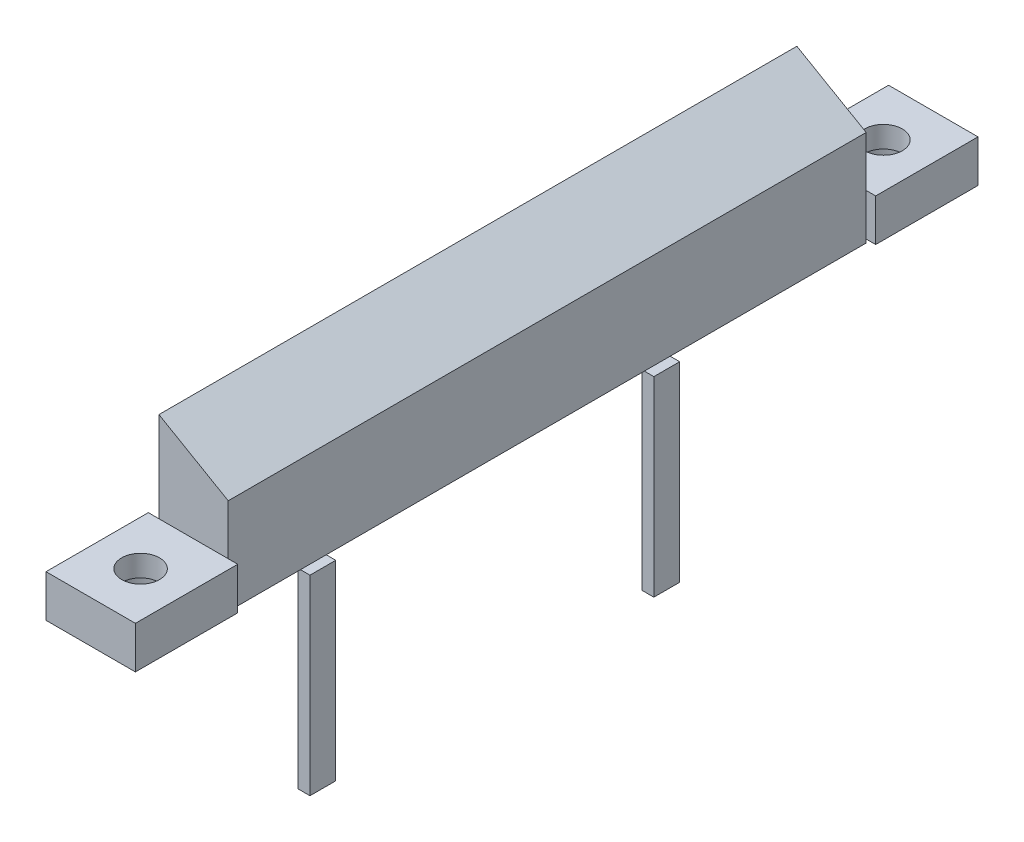
SolidWorks part; units mm, degrees
ref_plane "Front Plane" through (0, 0, 0) normal (0, 0, 1) x (1, 0, 0)
ref_plane "Top Plane" through (0, 0, 0) normal (0, 1, 0) x (1, 0, 0)
ref_plane "Right Plane" through (0, 0, 0) normal (1, 0, 0) x (0, 0, -1)
other "Configuration Table"
sketch "Sketch1" plane through (0, 0, 0) normal (0, 0, 1) x (1, 0, 0)
  line L0 (13.3671, 18.8) -> (17.3973, 18.8)
  line L1 (17.3973, 18.8) -> (17.3973, 24.3701)
  line L2 (17.3973, 24.3701) -> (13.3671, 26.6969)
  line L3 (13.3671, 26.6969) -> (13.3671, 18.8)
extrude "Clamp +X cover" add sketch "Sketch1" along normal blind 37.1 from offset 20.15
sketch "Sketch2" plane through (0, 0, 0) normal (0, 0, 1) x (1, 0, 0)
  line L0 (12.75, 19) -> (17.95, 19)
  line L1 (17.95, 19) -> (17.95, 21.45)
  line L2 (17.95, 21.45) -> (12.75, 21.45)
  line L3 (12.75, 21.45) -> (12.75, 19)
extrude "Ear +X cover -26" add sketch "Sketch2" along normal blind 5.95 from offset 26.1
sketch "Sketch3" plane through (0, 0, 0) normal (0, 0, 1) x (1, 0, 0)
  line L0 (12.75, 19) -> (17.95, 19)
  line L1 (17.95, 19) -> (17.95, 21.45)
  line L2 (17.95, 21.45) -> (12.75, 21.45)
  line L3 (12.75, 21.45) -> (12.75, 19)
extrude "Ear +X cover 17" add sketch "Sketch3" along normal blind 5.95 from offset 16.95
sketch "Sketch4" plane through (0, 0, 0) normal (0, 1, 0) x (1, 0, 0)
  circle A0 centre (15.35, 23.2) radius 1.1
  circle A1 centre (15.35, -20) radius 1.1
extrude "Cut-Extrude1" cut sketch "Sketch4" along normal blind 2.65 from offset 18.9
sketch "Sketch5" plane through (0, 0, 0) normal (0, 1, 0) x (1, 0, 0)
  circle A0 centre (15.35, 23.2) radius 2
  circle A1 centre (15.35, -20) radius 2
extrude "Cut-Extrude2" cut sketch "Sketch5" along normal blind 1.22 from offset 18.99
sketch "Sketch6" plane through (0, 0, 0) normal (0, 1, 0) x (1, 0, 0)
  line L1 (17.25, 8.75) -> (17.95, 8.75)
  line L2 (17.25, 8.75) -> (17.25, 7.25)
  line L3 (17.25, 7.25) -> (17.95, 7.25)
  line L4 (17.95, 8.75) -> (17.95, 7.25)
extrude "Boss-Extrude4" add sketch "Sketch6" along normal blind 11.11 from offset 7.69
sketch "Sketch7" plane through (0, 0, 0) normal (0, 1, 0) x (1, 0, 0)
  line L1 (17.25, -11.25) -> (17.95, -11.25)
  line L2 (17.25, -11.25) -> (17.25, -12.75)
  line L3 (17.25, -12.75) -> (17.95, -12.75)
  line L4 (17.95, -11.25) -> (17.95, -12.75)
extrude "Boss-Extrude5" add sketch "Sketch7" along normal blind 11.11 from offset 7.69
